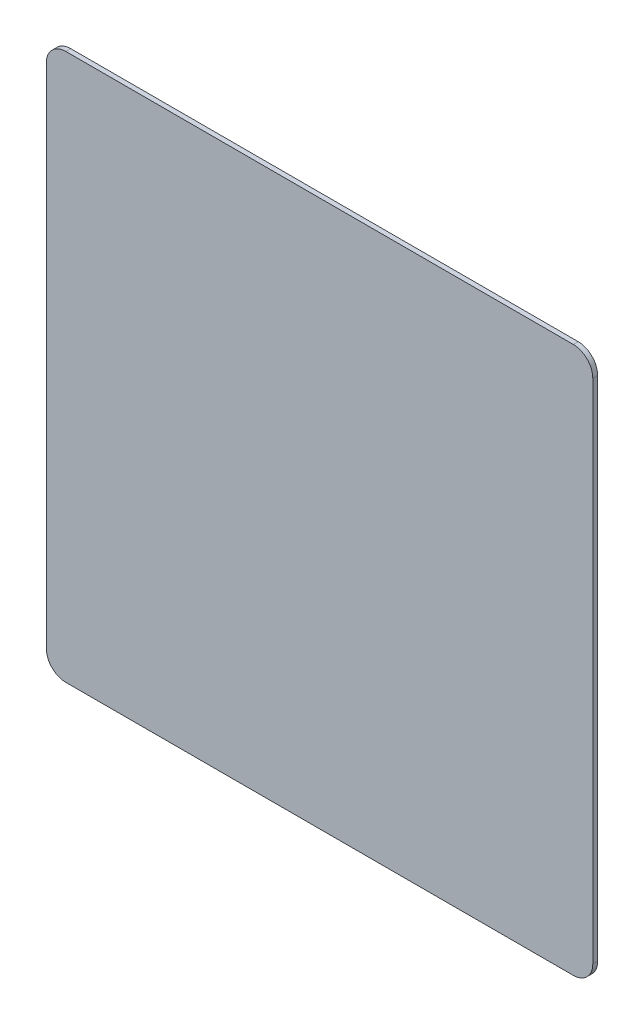
SolidWorks part; units mm, degrees
material "PW80:Mi:0:30:C1:0:1:2:Re:16:"
ref_plane "Plan1" through (0, 0, 0) normal (0, 0, 1) x (1, 0, 0)
ref_plane "Plan2" through (0, 0, 0) normal (0, 1, 0) x (1, 0, 0)
ref_plane "Plan3" through (0, 0, 0) normal (1, 0, 0) x (0, 0, -1)
sketch "Esquisse1" plane through (0, 0, 0) normal (0, 0, 1) x (1, 0, 0)
  line L1 (-30, 30) -> (30, 30)
  line L2 (-30, 30) -> (-30, -30)
  line L3 (-30, -30) -> (30, -30)
  line L4 (30, 30) -> (30, -30)
extrude "Base-Extrusion" add sketch "Esquisse1" along normal blind 7
sketch "Esquisse4" plane through (0, 0, 7) normal (0, 0, 1) x (1, 0, 0)
  line L1 (-28, 28) -> (28, 28)
  line L2 (-28, 28) -> (-28, -28)
  line L3 (-28, -28) -> (28, -28)
  line L4 (28, 28) -> (28, -28)
extrude "Boss.-Extru.2" add sketch "Esquisse4" along normal blind 0.5
fillet "Congé3" radius 2
sketch "Esquisse5" plane through (0, 0, 0) normal (0, 0, -1) x (-1, 0, 0)
  line L1 (-30, -30) -> (30, -30)
  line L2 (-30, -30) -> (-30, 30)
  line L3 (-30, 30) -> (30, 30)
  line L4 (30, -30) -> (30, 30)
extrude "Enlèv. mat.-Extru.2" cut sketch "Esquisse5" against normal blind 7
